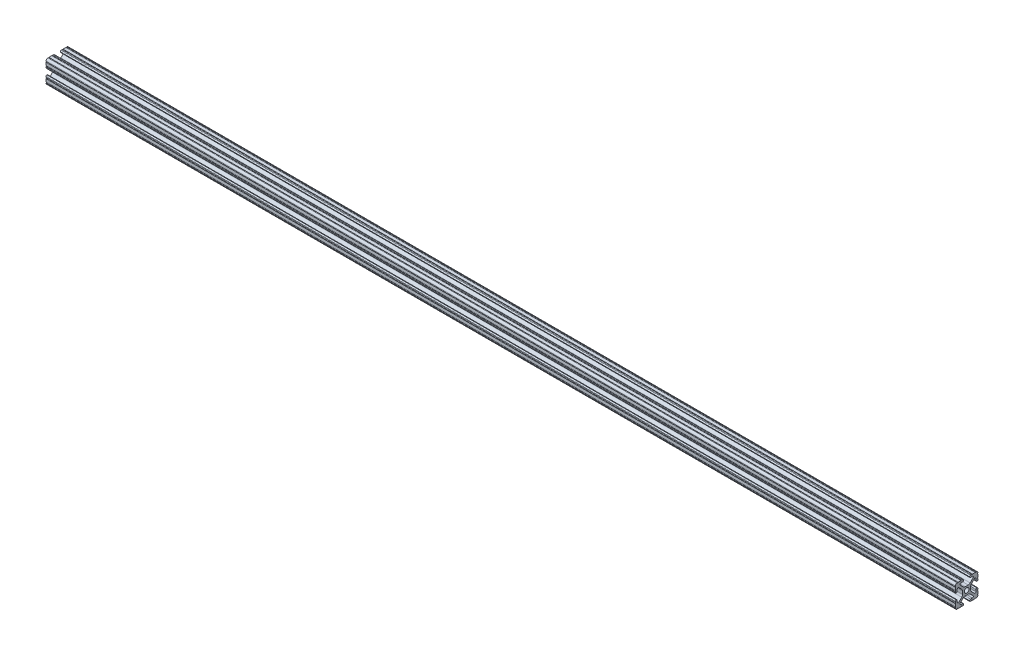
SolidWorks part; units mm, degrees
material "6061-T6 (SS)"
ref_plane "Front Plane" through (0, 0, 0) normal (0, 0, 1) x (1, 0, 0)
ref_plane "Top Plane" through (0, 0, 0) normal (0, 1, 0) x (1, 0, 0)
ref_plane "Right Plane" through (0, 0, 0) normal (1, 0, 0) x (0, 0, -1)
sketch "Sketch1" plane through (0, 0, 0) normal (1, 0, 0) x (0, 0, -1)
  line L0 (6.3331, -12.7) -> (9.5504, -12.7)
  line L1 (12.7, -9.5504) -> (12.7, -6.3331)
  line L2 (12.7, -5.3171) -> (12.7, -4.2875)
  line L3 (11.651, -3.2385) -> (11.5392, -3.2385)
  line L4 (10.4902, -4.2875) -> (10.4902, -6.4021)
  line L5 (8.7371, -7.1294) -> (5.441, -3.8408)
  line L6 (4.5085, -1.5932) -> (4.5085, 1.5932)
  line L7 (5.441, 3.8408) -> (8.7371, 7.1294)
  line L8 (10.4902, 6.4021) -> (10.4902, 4.2875)
  line L9 (11.5392, 3.2385) -> (11.651, 3.2385)
  line L10 (12.7, 4.2875) -> (12.7, 5.3171)
  line L11 (12.7, 6.3331) -> (12.7, 9.5504)
  line L12 (9.5504, 12.7) -> (6.3331, 12.7)
  line L13 (5.3171, 12.7) -> (4.2875, 12.7)
  line L14 (3.2385, 11.651) -> (3.2385, 11.5392)
  line L15 (4.2875, 10.4902) -> (6.4768, 10.4902)
  line L16 (7.207, 8.7244) -> (3.8983, 5.4232)
  line L17 (1.6558, 4.4958) -> (-1.6558, 4.4958)
  line L18 (-3.8983, 5.4232) -> (-7.207, 8.7244)
  line L19 (-6.4768, 10.4902) -> (-4.2875, 10.4902)
  line L20 (-3.2385, 11.5392) -> (-3.2385, 11.651)
  line L21 (-4.2875, 12.7) -> (-5.3171, 12.7)
  line L22 (-6.3331, 12.7) -> (-9.5504, 12.7)
  line L23 (-12.7, 9.5504) -> (-12.7, 6.3331)
  line L24 (-12.7, 5.3171) -> (-12.7, 4.2875)
  line L25 (-11.651, 3.2385) -> (-11.5392, 3.2385)
  line L26 (-10.4902, 4.2875) -> (-10.4902, 6.4021)
  line L27 (-8.7371, 7.1294) -> (-5.441, 3.8408)
  line L28 (-4.5085, 1.5932) -> (-4.5085, -1.5932)
  line L29 (-5.441, -3.8408) -> (-8.7371, -7.1294)
  line L30 (-10.4902, -6.4021) -> (-10.4902, -4.2875)
  line L31 (-11.5392, -3.2385) -> (-11.651, -3.2385)
  line L32 (-12.7, -4.2875) -> (-12.7, -5.3171)
  line L33 (-12.7, -6.3331) -> (-12.7, -9.5504)
  line L34 (-9.5504, -12.7) -> (-6.3331, -12.7)
  line L35 (-5.3171, -12.7) -> (-4.2875, -12.7)
  line L36 (-3.2385, -11.651) -> (-3.2385, -11.5392)
  line L37 (-4.2875, -10.4902) -> (-6.4164, -10.4902)
  line L38 (-7.1797, -8.6452) -> (-3.9523, -5.4237)
  line L39 (-1.7093, -4.4958) -> (1.7093, -4.4958)
  line L40 (3.9523, -5.4237) -> (7.1797, -8.6452)
  line L41 (6.4164, -10.4902) -> (4.2875, -10.4902)
  line L42 (3.2385, -11.5392) -> (3.2385, -11.651)
  line L43 (4.2875, -12.7) -> (5.3171, -12.7)
  circle A0 centre (0, 0) radius 2.6035
  arc A1 (6.3331, -12.7) -> (5.3171, -12.7) centre (5.8251, -12.7) ccw
  arc A2 (10.5664, -12.6998) -> (9.5504, -12.7) centre (10.0584, -12.7) ccw
  arc A3 (10.5664, -12.6998) -> (12.6998, -10.5664) centre (10.5918, -10.5918) ccw
  arc A4 (12.7, -9.5504) -> (12.6998, -10.5664) centre (12.7, -10.0584) ccw
  arc A5 (12.7, -5.3171) -> (12.7, -6.3331) centre (12.7, -5.8251) ccw
  arc A6 (12.7, -4.2875) -> (11.651, -3.2385) centre (11.651, -4.2875) ccw
  arc A7 (11.5392, -3.2385) -> (10.4902, -4.2875) centre (11.5392, -4.2875) ccw
  arc A8 (8.7371, -7.1294) -> (10.4902, -6.4021) centre (9.4628, -6.4021) ccw
  arc A9 (5.441, 3.8408) -> (4.5085, 1.5932) centre (7.6835, 1.5932) ccw
  arc A10 (10.4902, 6.4021) -> (8.7371, 7.1294) centre (9.4628, 6.4021) ccw
  arc A11 (10.4902, 4.2875) -> (11.5392, 3.2385) centre (11.5392, 4.2875) ccw
  arc A12 (11.651, 3.2385) -> (12.7, 4.2875) centre (11.651, 4.2875) ccw
  arc A13 (12.7, 6.3331) -> (12.7, 5.3171) centre (12.7, 5.8251) ccw
  arc A14 (12.6998, 10.5664) -> (12.7, 9.5504) centre (12.7, 10.0584) ccw
  arc A15 (12.6998, 10.5664) -> (10.5664, 12.6998) centre (10.5918, 10.5918) ccw
  arc A16 (9.5504, 12.7) -> (10.5664, 12.6998) centre (10.0584, 12.7) ccw
  arc A17 (5.3171, 12.7) -> (6.3331, 12.7) centre (5.8251, 12.7) ccw
  arc A18 (4.2875, 12.7) -> (3.2385, 11.651) centre (4.2875, 11.651) ccw
  arc A19 (3.2385, 11.5392) -> (4.2875, 10.4902) centre (4.2875, 11.5392) ccw
  arc A20 (7.207, 8.7244) -> (6.4768, 10.4902) centre (6.4768, 9.4563) ccw
  arc A21 (1.6558, 4.4958) -> (3.8983, 5.4232) centre (1.6558, 7.6708) ccw
  arc A22 (-3.8983, 5.4232) -> (-1.6558, 4.4958) centre (-1.6558, 7.6708) ccw
  arc A23 (-6.4768, 10.4902) -> (-7.207, 8.7244) centre (-6.4768, 9.4563) ccw
  arc A24 (-4.2875, 10.4902) -> (-3.2385, 11.5392) centre (-4.2875, 11.5392) ccw
  arc A25 (-3.2385, 11.651) -> (-4.2875, 12.7) centre (-4.2875, 11.651) ccw
  arc A26 (-6.3331, 12.7) -> (-5.3171, 12.7) centre (-5.8251, 12.7) ccw
  arc A27 (-10.5664, 12.6998) -> (-9.5504, 12.7) centre (-10.0584, 12.7) ccw
  arc A28 (-10.5664, 12.6998) -> (-12.6998, 10.5664) centre (-10.5918, 10.5918) ccw
  arc A29 (-12.7, 9.5504) -> (-12.6998, 10.5664) centre (-12.7, 10.0584) ccw
  arc A30 (-12.7, 5.3171) -> (-12.7, 6.3331) centre (-12.7, 5.8251) ccw
  arc A31 (-12.7, 4.2875) -> (-11.651, 3.2385) centre (-11.651, 4.2875) ccw
  arc A32 (-11.5392, 3.2385) -> (-10.4902, 4.2875) centre (-11.5392, 4.2875) ccw
  arc A33 (-8.7371, 7.1294) -> (-10.4902, 6.4021) centre (-9.4628, 6.4021) ccw
  arc A34 (-4.5085, 1.5932) -> (-5.441, 3.8408) centre (-7.6835, 1.5932) ccw
  arc A35 (-5.441, -3.8408) -> (-4.5085, -1.5932) centre (-7.6835, -1.5932) ccw
  arc A36 (-10.4902, -6.4021) -> (-8.7371, -7.1294) centre (-9.4628, -6.4021) ccw
  arc A37 (-10.4902, -4.2875) -> (-11.5392, -3.2385) centre (-11.5392, -4.2875) ccw
  arc A38 (-11.651, -3.2385) -> (-12.7, -4.2875) centre (-11.651, -4.2875) ccw
  arc A39 (-12.7, -6.3331) -> (-12.7, -5.3171) centre (-12.7, -5.8251) ccw
  arc A40 (-12.6998, -10.5664) -> (-12.7, -9.5504) centre (-12.7, -10.0584) ccw
  arc A41 (-12.6998, -10.5664) -> (-10.5664, -12.6998) centre (-10.5918, -10.5918) ccw
  arc A42 (-9.5504, -12.7) -> (-10.5664, -12.6998) centre (-10.0584, -12.7) ccw
  arc A43 (-5.3171, -12.7) -> (-6.3331, -12.7) centre (-5.8251, -12.7) ccw
  arc A44 (-4.2875, -12.7) -> (-3.2385, -11.651) centre (-4.2875, -11.651) ccw
  arc A45 (-3.2385, -11.5392) -> (-4.2875, -10.4902) centre (-4.2875, -11.5392) ccw
  arc A46 (-7.1797, -8.6452) -> (-6.4164, -10.4902) centre (-6.4164, -9.4098) ccw
  arc A47 (-1.7093, -4.4958) -> (-3.9523, -5.4237) centre (-1.7093, -7.6708) ccw
  arc A48 (3.9523, -5.4237) -> (1.7093, -4.4958) centre (1.7093, -7.6708) ccw
  arc A49 (6.4164, -10.4902) -> (7.1797, -8.6452) centre (6.4164, -9.4098) ccw
  arc A50 (4.2875, -10.4902) -> (3.2385, -11.5392) centre (4.2875, -11.5392) ccw
  arc A51 (3.2385, -11.651) -> (4.2875, -12.7) centre (4.2875, -11.651) ccw
  arc A52 (5.441, -3.8408) -> (4.5085, -1.5932) centre (7.6835, -1.5932) cw
  dimension "D1" = 3.175
extrude "Boss-Extrude1" add sketch "Sketch1" along normal mid plane 1016
